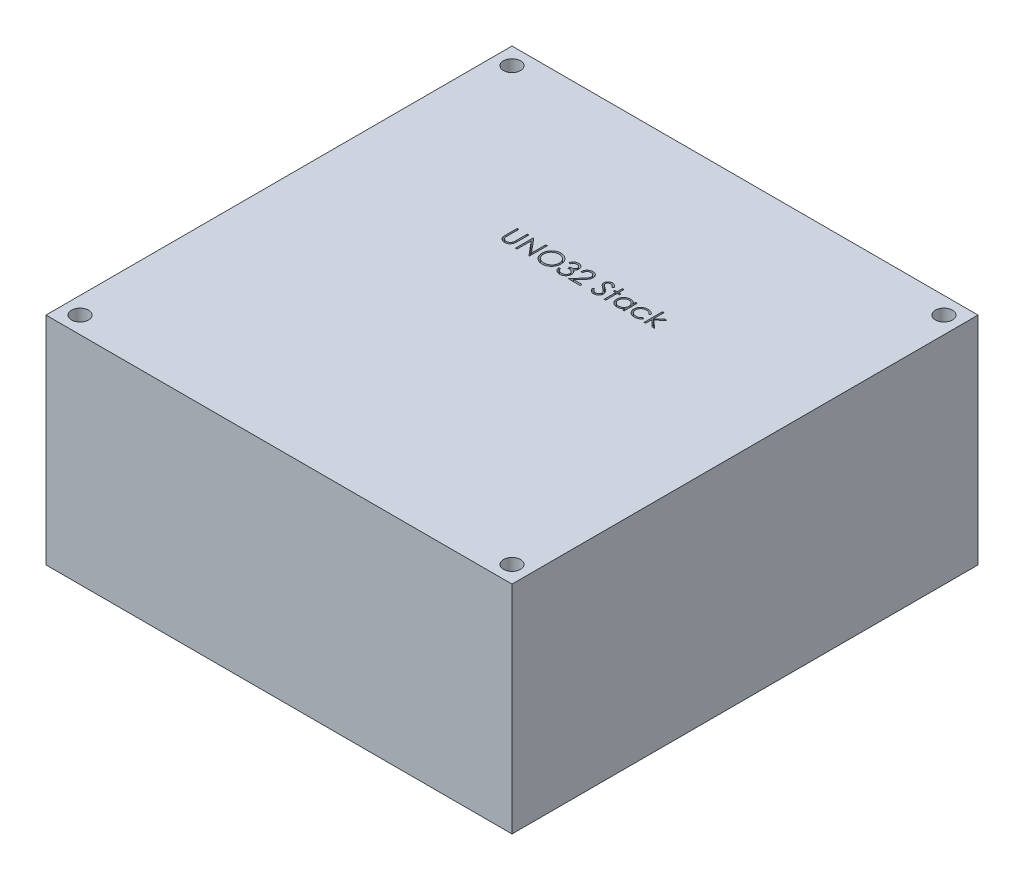
SolidWorks part; units mm, degrees
ref_plane "Front Plane" through (0, 0, 0) normal (0, 0, 1) x (1, 0, 0)
ref_plane "Top Plane" through (0, 0, 0) normal (0, 1, 0) x (1, 0, 0)
ref_plane "Right Plane" through (0, 0, 0) normal (1, 0, 0) x (0, 0, -1)
sketch "Sketch1" plane through (0, 0, 0) normal (0, 1, 0) x (1, 0, 0)
  line L1 (0, 0) -> (82.042, 0)
  line L2 (0, 0) -> (0, 82.042)
  line L3 (0, 82.042) -> (82.042, 82.042)
  line L4 (82.042, 0) -> (82.042, 82.042)
  dimension "D1" = 82.042
  dimension "D2" = 82.042
extrude "Boss-Extrude1" add sketch "Sketch1" along normal blind 38.1
sketch "Sketch2" plane through (0, 38.1, 0) normal (0, 1, 0) x (1, 0, 0)
  line L0 (0, 82.042) -> (0, 0) construction
  line L1 (82.042, 82.042) -> (0, 82.042) construction
  line L2 (41.021, 82.042) -> (41.021, 0) construction
  line L3 (0, 0) -> (82.042, 0) construction
  line L4 (0, 41.021) -> (82.042, 41.021) construction
  line L5 (82.042, 0) -> (82.042, 82.042) construction
  circle A0 centre (3, 79.042) radius 1.5
  circle A1 centre (79.042, 79.042) radius 1.5
  circle A2 centre (79.042, 3) radius 1.5
  circle A3 centre (3, 3) radius 1.5
  dimension "D1" = 3
  dimension "D2" = 3
  dimension "D3" = 3
extrude "Cut-Extrude1" cut sketch "Sketch2" against normal blind 50.8
sketch "Sketch4" plane through (0, 38.1, 0) normal (0, 1, 0) x (1, 0, 0)
  text T0 "UNO32 Stack "
extrude "Cut-Extrude2" cut sketch "Sketch4" against normal blind 1.27
